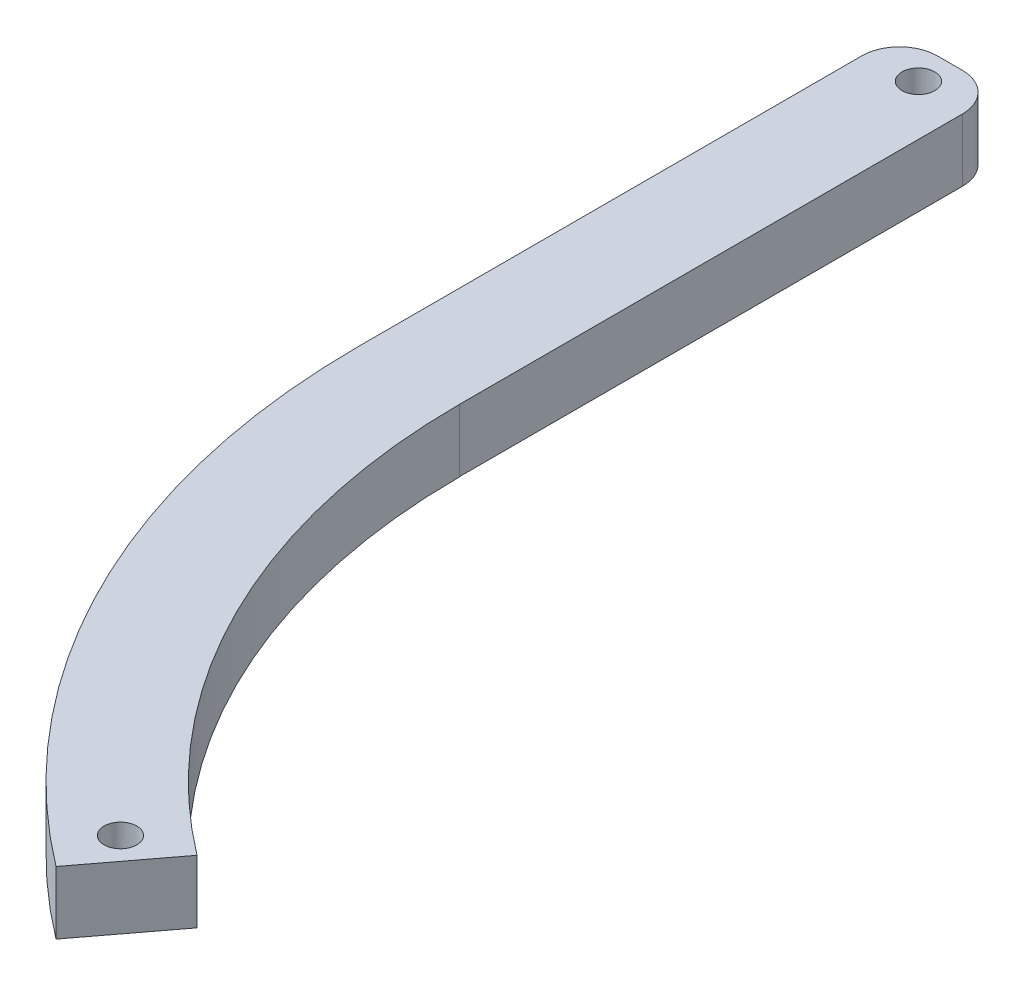
SolidWorks part; units mm, degrees
ref_plane "Front Plane" through (0, 0, 0) normal (0, 0, 1) x (1, 0, 0)
ref_plane "Top Plane" through (0, 0, 0) normal (0, 1, 0) x (1, 0, 0)
ref_plane "Right Plane" through (0, 0, 0) normal (1, 0, 0) x (0, 0, -1)
sketch "Sketch1" plane through (0, 0, 0) normal (0, 1, 0) x (1, 0, 0)
  line L0 (-76.2, 0) -> (-66.04, 0)
  line L1 (-46.0001, -60.749) -> (-39.8667, -52.6491)
  circle A0 centre (0, 0) radius 76.2
  circle A1 centre (0, 0) radius 66.04
extrude "Boss-Extrude1" add sketch "Sketch1" along normal blind 6.35
sketch "Sketch2" plane through (0, 0, 0) normal (0, 0, -1) x (-1, 0, 0)
  line L0 (66.04, 6.35) -> (76.2, 6.35)
  line L1 (66.04, 6.35) -> (66.04, 0.0233)
  line L2 (76.2, 6.35) -> (76.2, 0.0233)
  line L3 (66.04, 0.0233) -> (76.2, 0.0233)
extrude "Boss-Extrude2" add sketch "Sketch2" along normal blind 54.61
sketch "Sketch3" plane through (0, 6.35, 0) normal (0, 1, 0) x (1, 0, 0)
  line L0 (-71.12, 54.61) -> (-71.12, 51.435) construction
  line L1 (-76.2, 54.61) -> (-66.04, 54.61) construction
  circle A0 centre (-71.12, 51.435) radius 1.651
extrude "Cut-Extrude1" cut sketch "Sketch3" against normal blind 6.35
sketch "Sketch4" plane through (0, 6.35, 0) normal (0, 1, 0) x (1, 0, 0)
  line L0 (-42.9334, -56.699) -> (-45.4646, -54.7824) construction
  line L7 (-46.0001, -60.749) -> (-39.8667, -52.6491) construction
  circle A6 centre (-45.4646, -54.7824) radius 1.651
extrude "Cut-Extrude2" cut sketch "Sketch4" against normal blind 22.606
fillet "Fillet1" radius 3.81 2 edges at (-76.2, 3.1867, -54.61) (-66.04, 3.1867, -54.61)
